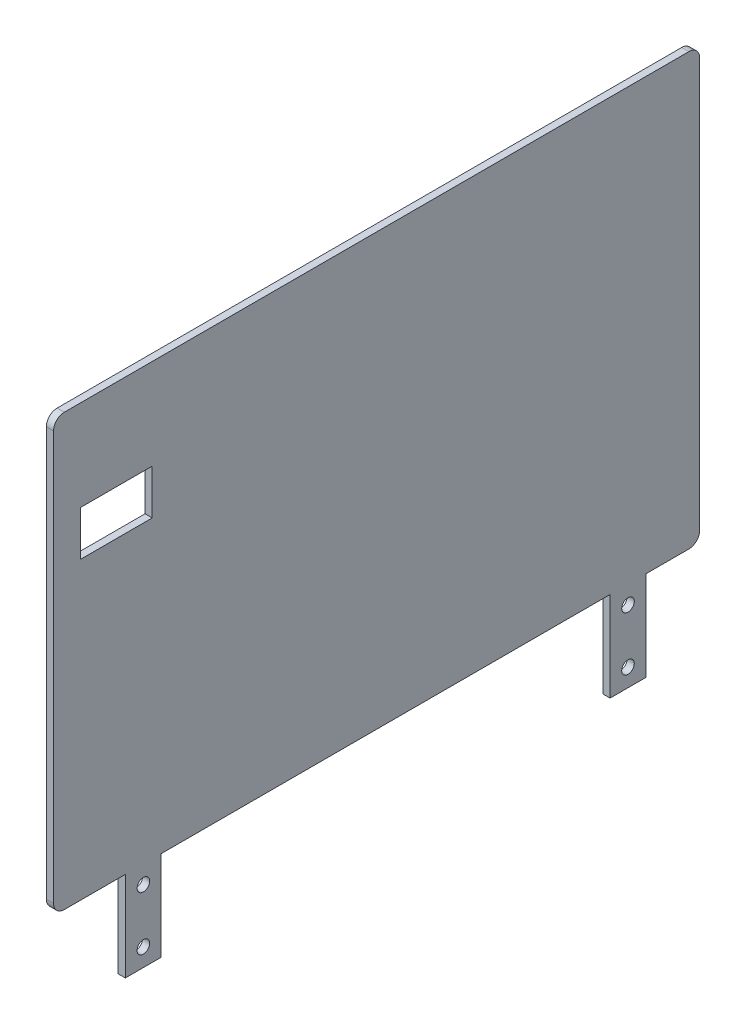
SolidWorks part; units mm, degrees
material "Acrylic (Medium-high impact)"
ref_plane "Front Plane" through (0, 0, 0) normal (0, 0, 1) x (1, 0, 0)
ref_plane "Top Plane" through (0, 0, 0) normal (0, 1, 0) x (1, 0, 0)
ref_plane "Right Plane" through (0, 0, 0) normal (1, 0, 0) x (0, 0, -1)
sketch "Sketch2" plane through (0, 0, 0) normal (1, 0, 0) x (0, 0, -1)
  line L1 (-180, -154) -> (180, -154)
  line L2 (-180, -154) -> (-180, 86)
  line L3 (-180, 86) -> (180, 86)
  line L4 (180, -154) -> (180, 86)
  line L5 (-180, -154) -> (180, 86) construction
  line L6 (-180, 86) -> (180, -154) construction
  point P0 (0, -34)
  dimension "D1" = 360
  dimension "D2" = 240
  dimension "D3" = 34
extrude "Boss-Extrude2" add sketch "Sketch2" along normal mid plane 4
fillet "Fillet1" radius 6 4 edges at (0, -154, -180) (0, -154, 180) (0, 86, 180) (0, 86, -180)
sketch "Sketch3" plane through (2, 0, 0) normal (1, 0, 0) x (0, 0, -1)
  line L0 (174, 86) -> (-174, 86) construction
  line L1 (-165, 10.5) -> (-125, 10.5)
  line L2 (-165, 10.5) -> (-165, 35.5)
  line L3 (-165, 35.5) -> (-125, 35.5)
  line L4 (-125, 10.5) -> (-125, 35.5)
  line L5 (-165, 10.5) -> (-125, 35.5) construction
  line L6 (-165, 35.5) -> (-125, 10.5) construction
  line L7 (-180, 80) -> (-180, -148) construction
  point P0 (-145, 23)
  dimension "D1" = 25
  dimension "D2" = 40
  dimension "D3" = 50.5
  dimension "D4" = 15
extrude "Cut-Extrude1" cut sketch "Sketch3" against normal through all
sketch "Sketch4" plane through (0, 0, 0) normal (1, 0, 0) x (0, 0, -1)
  line L0 (-174, -154) -> (174, -154) construction
  line L1 (-140, -154) -> (-120, -154)
  line L2 (-140, -154) -> (-140, -204)
  line L3 (-140, -204) -> (-120, -204)
  line L4 (-120, -154) -> (-120, -204)
  line L5 (150.0747, -154) -> (130.0747, -154)
  line L6 (150.0747, -154) -> (150.0747, -204)
  line L7 (150.0747, -204) -> (130.0747, -204)
  line L8 (130.0747, -154) -> (130.0747, -204)
  point P8 (140.0747, -194)
  point P11 (-129.9251, -164)
  point P12 (140.0747, -164)
  point P15 (-129.9253, -194)
  dimension "D1" = 20
  dimension "D2" = 30
  dimension "D3" = 50
  dimension "D4" = 30
  dimension "D5" = 20
  dimension "D6" = 50
  dimension "D7" = 10
  dimension "D8" = 10
  dimension "D9" = 10
  dimension "D10" = 10
  dimension "D11" = 270
  dimension "D12" = 140
  dimension "D13" = 150.0747
  dimension "D14" = 129.9251
extrude "Boss-Extrude3" add sketch "Sketch4" along normal mid plane 4
sketch "Sketch10" plane through (2, 0, 0) normal (1, 0, 0) x (0, 0, -1)
  line L0 (150.0747, -204) -> (150.0747, -154) construction
  line L1 (130.0747, -204) -> (150.0747, -204) construction
  point P0 (-129.9253, -194)
  point P1 (-129.9253, -164)
  point P2 (140.0747, -194)
  point P3 (140.0747, -164)
  dimension "D1" = 270
  dimension "D2" = 270
  dimension "D3" = 10
  dimension "D4" = 10
  dimension "D5" = 10
  dimension "D6" = 30
  dimension "D7" = 194
  dimension "D8" = 164
hole_wizard "M8x1.0 Tapped Hole1" positions "Sketch10" profile "Sketch12" tap size "M8x1.0" standard "ANSI Metric" end condition through all
sketch "Sketch12" plane through (2, -194, 129.9253) normal (0, 1, 0) x (0, 0, -1)
  line L0 (0, 0) -> (0, 4)
  line L1 (0, 4) -> (3.5, 4)
  line L2 (3.5, 4) -> (3.5, 0)
  line L5 (3.5, 0) -> (0, 0)
  line L11 (0, -6.35) -> (0, 107.95) construction
  dimension "Thru Tap Drill Dia." = 7
  dimension "Thru Tap Drill Depth" = 4
cosmetic thread "Hole Thread1" parameters "D2"=8
cosmetic thread "Hole Thread2" parameters "D2"=8
cosmetic thread "Hole Thread3" parameters "D2"=8
cosmetic thread "Hole Thread4" parameters "D2"=8
